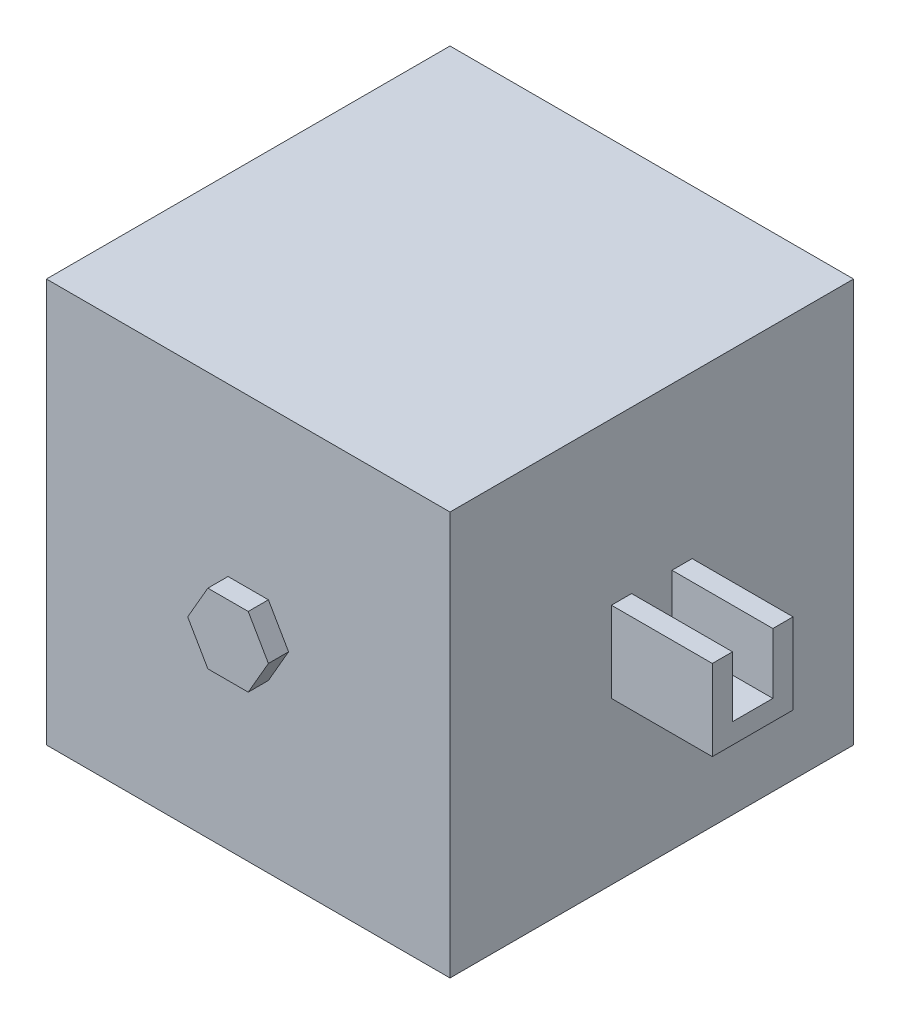
SolidWorks part; units mm, degrees
ref_plane "Front Plane" through (0, 0, 0) normal (0, 0, 1) x (1, 0, 0)
ref_plane "Top Plane" through (0, 0, 0) normal (0, 1, 0) x (1, 0, 0)
ref_plane "Right Plane" through (0, 0, 0) normal (1, 0, 0) x (0, 0, -1)
sketch "Sketch1" plane through (0, 0, 0) normal (0, 0, 1) x (1, 0, 0)
  line L1 (-25, -25) -> (25, -25)
  line L2 (-25, -25) -> (-25, 25)
  line L3 (-25, 25) -> (25, 25)
  line L4 (25, -25) -> (25, 25)
  point P0 (0, 0)
  dimension "D1" = 50
  dimension "D2" = 50
extrude "Boss-Extrude1" add sketch "Sketch1" along normal blind 50
sketch "Sketch2" plane through (-25, 0, 0) normal (-1, 0, 0) x (0, 0, 1)
  line L0 (0, 0) -> (50, 0)
  line L1 (50, 25) -> (50, -25) construction
  line L2 (25, -25) -> (25, 25)
  line L3 (50, -25) -> (0, -25) construction
  line L4 (50, 25) -> (0, 25) construction
  line L11 (20, 5) -> (30, 5)
  line L12 (20, 5) -> (20, -5)
  line L13 (20, -5) -> (30, -5)
  line L14 (30, 5) -> (30, -5)
  point P11 (25, 0)
  point P17 (25, 0)
  dimension "D1" = 10
  dimension "D2" = 10
  dimension "D3" = 5
  dimension "D4" = 5
extrude "Boss-Extrude2" add sketch "Sketch2" along normal blind 12.5 contours L14 L0 L2 L13 | L12 L13 L2 L0 | L11 L12 L0 L2 | L14 L11 L2 L0
sketch "Sketch3" plane through (-37.5, 0, 0) normal (-1, 0, 0) x (0, 0, 1)
  line L7 (20, -5) -> (30, -5) construction
  line L9 (22.5, 5) -> (22.5, -2.5)
  line L10 (22.5, -2.5) -> (27.5, -2.5)
  line L11 (27.5, -2.5) -> (27.5, 5)
  line L12 (27.5, 5) -> (22.5, 5)
  dimension "D1" = 7.5
  dimension "D2" = 5
  dimension "D4" = 2.5
extrude "Cut-Extrude1" cut sketch "Sketch3" against normal blind 12.5
sketch "Sketch6" plane through (25, 0, 0) normal (1, 0, 0) x (0, 0, -1)
  line L6 (-20, -5) -> (-30, -5)
  line L7 (-20, -5) -> (-20, 5)
  line L8 (-20, 5) -> (-30, 5)
  line L9 (-30, -5) -> (-30, 5)
  point P5 (-25, 0)
extrude "Boss-Extrude3" add sketch "Sketch6" along normal blind 12.5
sketch "Sketch7" plane through (37.5, 0, 0) normal (1, 0, 0) x (0, 0, -1)
  line L0 (-30, -5) -> (-20, -5) construction
  line L1 (-27.5, -2.5) -> (-22.5, -2.5)
  line L2 (-27.5, -2.5) -> (-27.5, 5)
  line L3 (-27.5, 5) -> (-22.5, 5)
  line L4 (-22.5, -2.5) -> (-22.5, 5)
  line L7 (-20, -5) -> (-20, 5) construction
  line L8 (-30, 5) -> (-30, -5) construction
  point P0 (-25, 1.25)
  dimension "D1" = 2.5
  dimension "D2" = 2.5
  dimension "D3" = 2.5
  dimension "D4" = 7.5
extrude "Cut-Extrude2" cut sketch "Sketch7" against normal blind 12.5
sketch "Sketch16" plane through (0, 0, 50) normal (0, 0, 1) x (1, 0, 0)
  line L1 (5, 0) -> (2.5, 4.3301)
  line L2 (2.5, 4.3301) -> (-2.5, 4.3301)
  line L3 (-2.5, 4.3301) -> (-5, 0)
  line L4 (-5, 0) -> (-2.5, -4.3301)
  line L5 (-2.5, -4.3301) -> (2.5, -4.3301)
  line L6 (2.5, -4.3301) -> (5, 0)
  circle A0 centre (0, 0) radius 4.3301 construction
  dimension "D1" = 5
extrude "Boss-Extrude5" add sketch "Sketch16" along normal blind 2.5
sketch "Sketch17" plane through (0, 0, 0) normal (0, 0, -1) x (-1, 0, 0)
  line L1 (5, 0) -> (2.5, 4.3301)
  line L2 (2.5, 4.3301) -> (-2.5, 4.3301)
  line L3 (-2.5, 4.3301) -> (-5, 0)
  line L4 (-5, 0) -> (-2.5, -4.3301)
  line L5 (-2.5, -4.3301) -> (2.5, -4.3301)
  line L6 (2.5, -4.3301) -> (5, 0)
  circle A0 centre (0, 0) radius 4.3301 construction
  dimension "D1" = 5
extrude "Boss-Extrude6" add sketch "Sketch17" along normal blind 2.5
